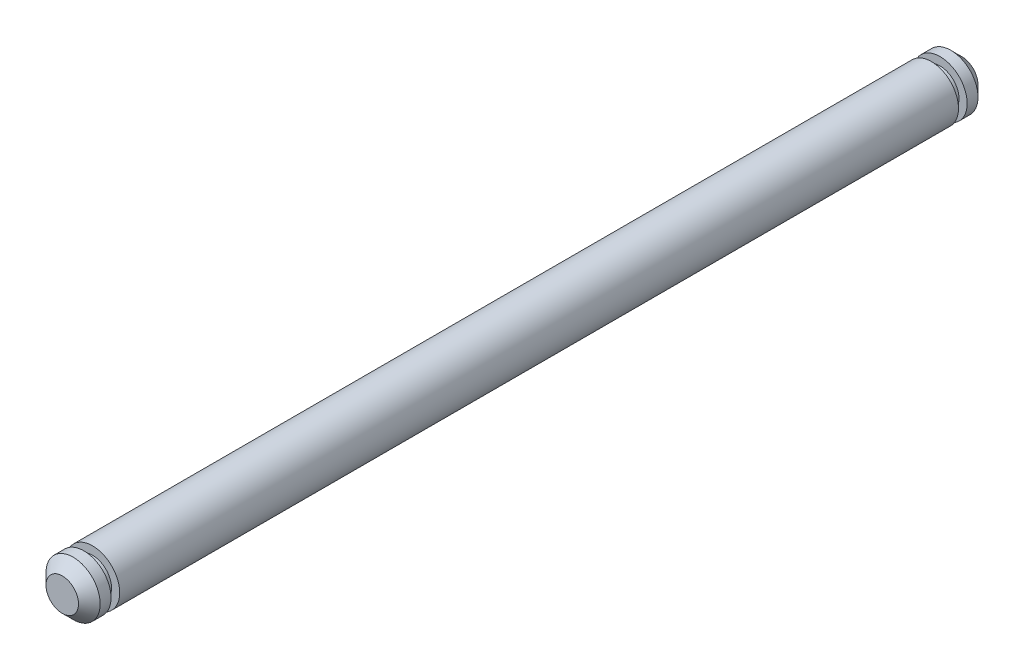
SolidWorks part; units mm, degrees
material "普通碳钢"
ref_plane "前视基准面" through (0, 0, 0) normal (0, 0, 1) x (1, 0, 0)
ref_plane "上视基准面" through (0, 0, 0) normal (0, 1, 0) x (1, 0, 0)
ref_plane "右视基准面" through (0, 0, 0) normal (1, 0, 0) x (0, 0, -1)
sketch "草图1" plane through (0, 0, 0) normal (0, 0, 1) x (1, 0, 0)
  circle A0 centre (0, 0) radius 2.5
  dimension "D1" = 5
extrude "凸台-拉伸1" add sketch "草图1" along normal mid plane 83
sketch "草图2" plane through (0, 0, 0) normal (0, 1, 0) x (1, 0, 0)
  line L0 (0, -49.4231) -> (0, 49.1204) construction
  line L1 (2.5, -41.5) -> (2.5, 41.5) construction
  line L2 (2.5, 38.7) -> (1.75, 38.7)
  line L3 (2.5, 38.7) -> (2.5, 39.5)
  line L4 (2.5, 39.5) -> (1.75, 39.5)
  line L5 (1.75, 38.7) -> (1.75, 39.5)
  line L6 (2.5, 41.5) -> (-2.5, 41.5) construction
  line L7 (0, 0) -> (23.9031, 0) construction
  line L8 (2.5, -38.7) -> (2.5, -39.5)
  line L9 (2.5, -38.7) -> (1.75, -38.7)
  line L10 (2.5, -39.5) -> (1.75, -39.5)
  line L11 (1.75, -38.7) -> (1.75, -39.5)
  dimension "D1" = 0.8
  dimension "D2" = 1.75
  dimension "D3" = 2
revolve "切除-旋转1" cut sketch "草图2" angle 360 about L0
chamfer "倒角1" distance 1 angle 45 2 edges at (2.5, 0, -41.5) (2.5, 0, 41.5)
